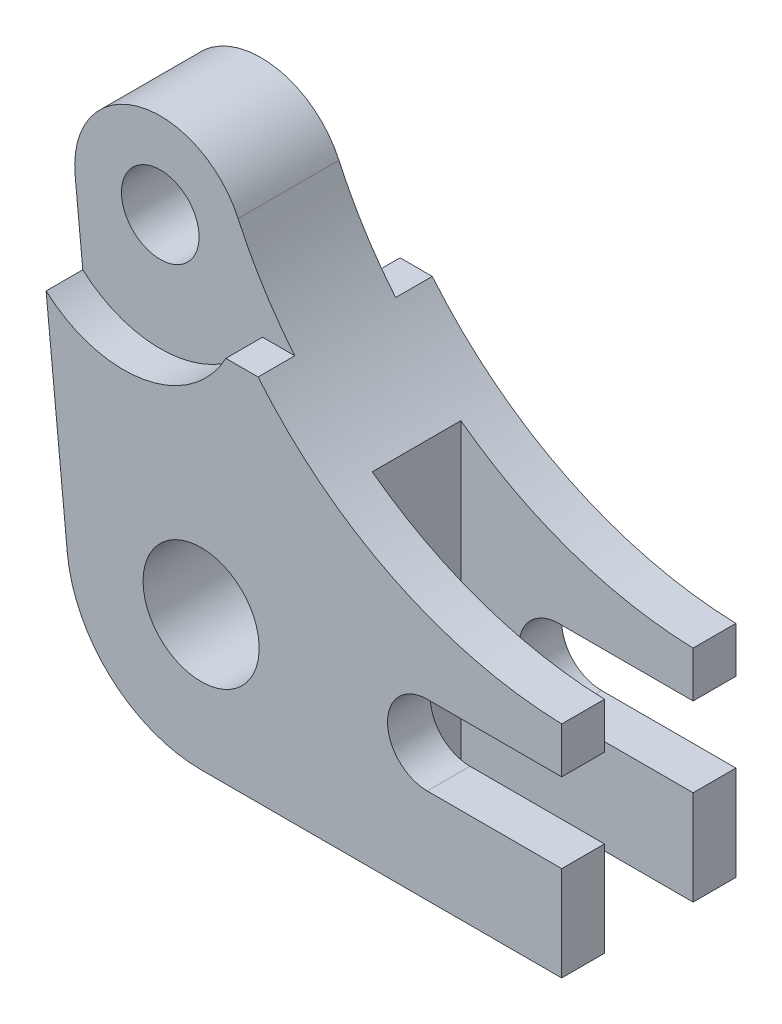
SolidWorks part; units mm, degrees
material "AISI 1020"
ref_plane "Plan de face" through (0, 0, 0) normal (0, 0, 1) x (1, 0, 0)
ref_plane "Plan de dessus" through (0, 0, 0) normal (0, 1, 0) x (1, 0, 0)
ref_plane "Plan de droite" through (0, 0, 0) normal (1, 0, 0) x (0, 0, -1)
sketch "Esquisse1" plane through (0, 0, 0) normal (0, 0, 1) x (1, 0, 0)
  line L0 (0, 0) -> (-12.6821, 47.3304) construction
  line L1 (-25.5355, 80.9701) -> (83.2336, 80.9701) construction
  line L2 (61.0021, 87.5844) -> (61.0021, -17.1484) construction
  line L3 (-26.6152, 45.9633) -> (-21.8949, -2.1482)
  line L4 (0, -22) -> (59, -22)
  line L5 (59, -22) -> (59, -6.5)
  line L6 (59, -6.5) -> (37, -6.5)
  line L7 (37, 6.5) -> (59, 6.5)
  line L8 (59, 6.5) -> (59, 14)
  line L9 (0, 0) -> (0, 31.0252) construction
  circle A0 centre (0, 0) radius 9.5
  arc A1 (-21.8949, -2.1482) -> (0, -22) centre (0, 0) ccw
  circle A2 centre (-12.6821, 47.3304) radius 6.35
  arc A3 (0.0534, 53.1446) -> (-26.6152, 45.9633) centre (-12.6821, 47.3304) ccw
  arc A4 (37, -6.5) -> (37, 6.5) centre (37, 0) cw
  arc A5 (59, 14) -> (0.0534, 53.1446) centre (61.0021, 80.9701) cw
  dimension "D3" = 14
  dimension "D4" = 22
  dimension "D7" = 12.7
  dimension "D8" = 19
  dimension "D9" = 6.5
  dimension "D11" = 67
  dimension "D1" = 59
  dimension "D2" = 36
  dimension "D5" = 15
  dimension "D6" = 49
  dimension "D10" = 22
extrude "Boss.-Extru.1" add sketch "Esquisse1" along normal mid plane 28.5
sketch "Esquisse2" plane through (0, 0, 14.25) normal (0, 0, 1) x (1, 0, 0)
  line L0 (-26.6152, 45.9633) -> (-21.8949, -2.1482) construction
  line L1 (4.0511, 38.3304) -> (9.3218, 38.3304)
  line L2 (-26.6152, 45.9633) -> (-25.361, 33.1795)
  arc A0 (-25.361, 33.1795) -> (4.0511, 38.3304) centre (-12.6821, 47.3304) ccw
  arc A1 (0.0534, 53.1446) -> (59, 14) centre (61.0021, 80.9701) ccw construction
  arc A2 (0.0534, 53.1446) -> (-26.6152, 45.9633) centre (-12.6821, 47.3304) ccw construction
  arc A3 (0.0534, 53.1446) -> (-26.6152, 45.9633) centre (-12.6821, 47.3304) ccw
  arc A4 (0.0534, 53.1446) -> (9.3218, 38.3304) centre (61.0021, 80.9701) ccw
  dimension "D1" = 19
  dimension "D2" = 9
extrude "Enlèv. mat.-Extru.1" cut sketch "Esquisse2" against normal blind 6
mirror "Symétrie1" about plane through (0, 0, 0) normal (0, 0, 1) of "Enlèv. mat.-Extru.1"
sketch "Esquisse3" plane through (0, 0, 0) normal (0, 0, 1) x (1, 0, 0)
  line L0 (21, -22) -> (21, 27.2222)
  line L1 (0, -22) -> (59, -22) construction
  line L2 (59, -22) -> (59, -6.5) construction
  line L3 (21, -22) -> (59, -22)
  line L4 (59, -22) -> (59, 14)
  arc A0 (9.3218, 38.3304) -> (59, 14) centre (61.0021, 80.9701) ccw construction
  arc A1 (21, 27.2222) -> (59, 14) centre (61.0021, 80.9701) ccw
  dimension "D1" = 38
extrude "Enlèv. mat.-Extru.2" cut sketch "Esquisse3" along normal offset from surface 7 and the other way offset from surface (7.25 mm away) 7 up to face at (24.0372, 5.542, 14.25) other way up to face at (9.5, 0, -14.25)
equation "\"A\"= 59"
equation "\"B\"= 22"
equation "\"C\"= 28.5"
equation "\"D1@Esquisse1\"=\"A\""
equation "\"D4@Esquisse1\"=\"B\""
equation "\"D1@Boss.-Extru.1\"=\"C\""
